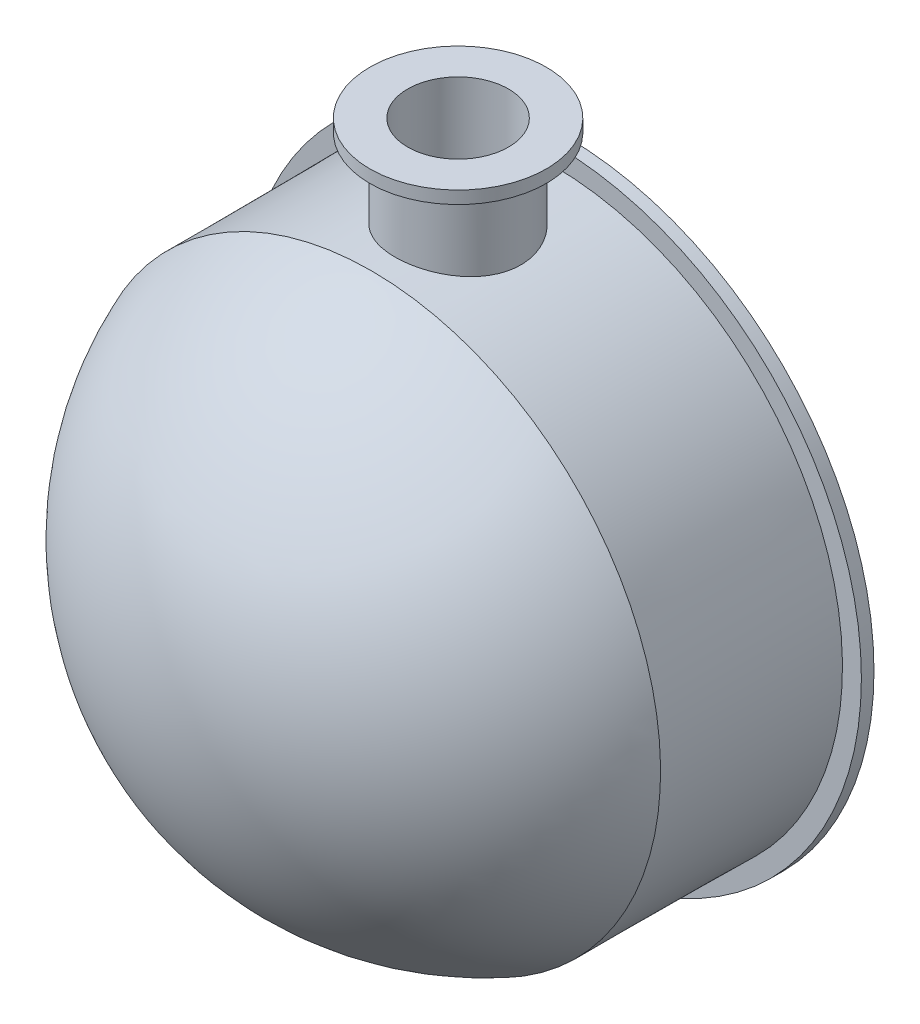
SolidWorks part; units mm, degrees
ref_plane "Front Plane" through (0, 0, 0) normal (0, 0, 1) x (1, 0, 0)
ref_plane "Top Plane" through (0, 0, 0) normal (0, 1, 0) x (1, 0, 0)
ref_plane "Right Plane" through (0, 0, 0) normal (1, 0, 0) x (0, 0, -1)
sketch "Sketch1" plane through (0, 0, 0) normal (1, 0, 0) x (0, 0, -1)
  line L0 (0, 0) -> (0, 220) construction
  line L1 (0, 0) -> (-300, 0) construction
  line L2 (0, 220) -> (0, 245)
  line L3 (0, 245) -> (-10, 245)
  line L4 (-10, 245) -> (-10, 230)
  line L6 (-150, 220) -> (0, 220)
  line L7 (-153.653, 229.3089) -> (-10, 230)
  line L9 (-300, 0) -> (-310, 0)
  arc A0 (-150, 220) -> (-300, 0) centre (-63.6667, 0) ccw
  arc A1 (-153.653, 229.3089) -> (-310, 0) centre (-63.6667, 0) ccw
  dimension "D1" = 220
  dimension "D2" = 25
  dimension "D3" = 10
  dimension "D4" = 10
  dimension "D5" = 150
  dimension "D6" = 300
revolve "Revolve1" add sketch "Sketch1" angle 360 about L1
ref_plane "Plane1" through (0, 300, 0) normal (0, 1, 0) x (1, 0, 0)
sketch "Sketch2" plane through (0, 300, 0) normal (0, 1, 0) x (1, 0, 0)
  line L0 (0, -10) -> (0, -85) construction
  line L1 (-230, -10) -> (230, -10) construction
  circle A0 centre (0, -85) radius 50
  dimension "D2" = 100
  dimension "D1" = 75
extrude "Boss-Extrude1" add sketch "Sketch2" against normal up to surface (70.6014 mm away)
sketch "Sketch3" plane through (0, 300, 0) normal (0, 1, 0) x (1, 0, 0)
  circle A2 centre (0, -85) radius 40
  circle A3 centre (0, -85) radius 40
  dimension "D1" = 10
extrude "Cut-Extrude1" cut sketch "Sketch3" against normal blind 104.902
sketch "Sketch4" plane through (0, 300, 0) normal (0, 1, 0) x (1, 0, 0)
  circle A0 centre (0, -85) radius 50 construction
  circle A1 centre (0, -85) radius 50
  circle A2 centre (0, -85) radius 70
  dimension "D1" = 20
extrude "Boss-Extrude2" add sketch "Sketch4" against normal blind 10
